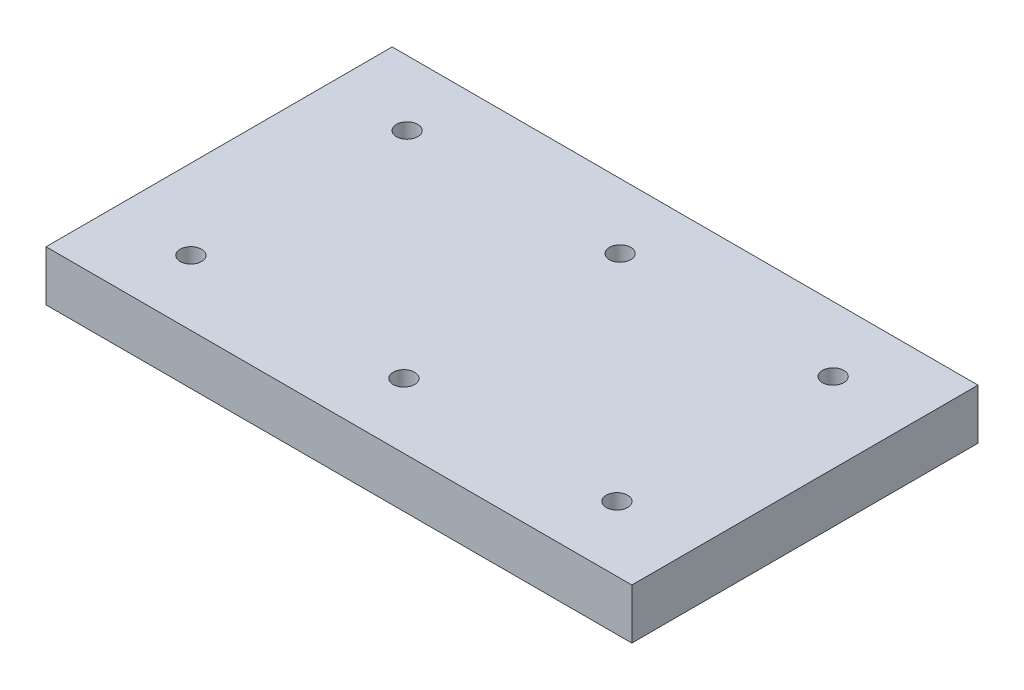
SolidWorks part; units mm, degrees
ref_plane "Front Plane" through (0, 0, 0) normal (0, 0, 1) x (1, 0, 0)
ref_plane "Top Plane" through (0, 0, 0) normal (0, 1, 0) x (1, 0, 0)
ref_plane "Right Plane" through (0, 0, 0) normal (1, 0, 0) x (0, 0, -1)
sketch "Sketch1" plane through (0, 0, 0) normal (0, 1, 0) x (1, 0, 0)
  line L1 (-69.85, -41.275) -> (69.85, -41.275)
  line L2 (-69.85, -41.275) -> (-69.85, 41.275)
  line L3 (-69.85, 41.275) -> (69.85, 41.275)
  line L4 (69.85, -41.275) -> (69.85, 41.275)
  line L5 (-69.85, -41.275) -> (69.85, 41.275) construction
  line L6 (-69.85, 41.275) -> (69.85, -41.275) construction
  point P0 (0, 0)
  dimension "D1" = 139.7
  dimension "D2" = 82.55
extrude "Boss-Extrude1" add sketch "Sketch1" along normal blind 12
sketch "Sketch2" plane through (0, 0, 0) normal (0, -1, 0) x (1, 0, 0)
  line L0 (-69.85, 0) -> (69.85, 0) construction
  line L1 (-69.85, -41.275) -> (-69.85, 41.275) construction
  line L2 (69.85, 41.275) -> (69.85, -41.275) construction
  line L3 (-69.85, 25.781) -> (69.85, 25.781) construction
  point P8 (-50.8, 25.781)
  point P9 (0, 25.781)
  point P11 (50.8, 25.781)
  point P12 (0, 0)
  point P13 (50.8, -25.781)
  point P14 (0, -25.781)
  point P15 (-50.8, -25.781)
  dimension "D1" = 25.781
  dimension "D2" = 19.05
  dimension "D3" = 19.05
hole_wizard "#10 Clearance Hole1" positions "Sketch3" profile "Sketch4" hole size "#10" standard "ANSI Inch" end condition through all
sketch "Sketch3" plane through (0, 0, 0) normal (0, -1, 0) x (-1, 0, 0)
  point P0 (-50.8, 25.781)
  point P3 (0, 25.781)
  point P6 (50.8, 25.781)
  point P9 (50.8, -25.781)
  point P12 (0, -25.781)
  point P15 (-50.8, -25.781)
sketch "Sketch4" plane through (50.8, 0, -25.781) normal (1, 0, 0) x (0, 0, -1)
  line L0 (0, 0) -> (0, 12)
  line L1 (0, 12) -> (2.5527, 12)
  line L2 (2.5527, 12) -> (2.5527, 0)
  line L5 (2.5527, 0) -> (0, 0)
  line L11 (0, -6.35) -> (0, 107.95) construction
  dimension "Thru Hole Dia." = 5.1054
  dimension "Thru Hole Depth" = 12
